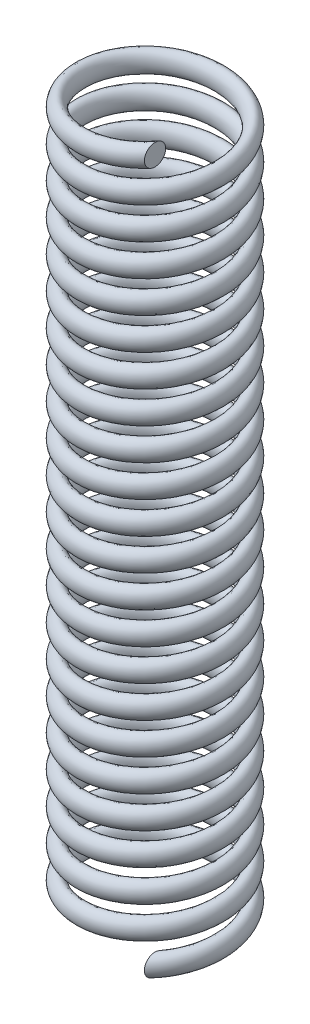
SolidWorks part; units mm, degrees
ref_plane "Front Plane" through (0, 0, 0) normal (0, 0, 1) x (1, 0, 0)
ref_plane "Top Plane" through (0, 0, 0) normal (0, 1, 0) x (1, 0, 0)
ref_plane "Right Plane" through (0, 0, 0) normal (1, 0, 0) x (0, 0, -1)
sketch "Sketch1" plane through (0, 0, 0) normal (0, 0, 1) x (1, 0, 0)
  line L0 (0, 17.5312) -> (0, -15.4688)
  dimension "D1" = 33
ref_plane "Plane1" through (0, 17.5312, 0) normal (0, 1, 0) x (1, 0, 0)
sketch "Sketch2" plane through (0, 17.5312, 0) normal (0, 1, 0) x (1, 0, 0)
  circle A0 centre (0, 0) radius 3.25
  dimension "D1" = 6.5
curve "Helix/Spiral1" pitch 1.5 height 33 turns 22
ref_plane "Plane2" through (2.2981, 0, 0) normal (1, 0, 0) x (0, 0, -1)
sketch "Sketch3" plane through (2.2981, 0, 0) normal (1, 0, 0) x (0, 0, -1)
  line L0 (3.6681, 17.5312) -> (-3.6681, 17.5312) construction
  circle A0 centre (-2.2981, 17.5312) radius 0.5
  spline S0 degree 3 poles (-2.2981, 17.5312) (-2.597, 17.5002) (-3.0817, 17.4374) (-3.3344, 17.3438) (-3.0808, 17.25) (-2.3579, 17.1563) (-1.2761, 17.0625) (0, 16.9688) (1.2761, 16.875) (2.3579, 16.7813) (3.0808, 16.6875) (3.3346, 16.5938) (3.0808, 16.5) (2.3579, 16.4063) (1.2761, 16.3125) (0, 16.2188) (-1.2761, 16.125) (-2.3579, 16.0313) (-3.0808, 15.9375) (-3.3346, 15.8438) (-3.0808, 15.75) (-2.3579, 15.6562) (-1.2761, 15.5625) (0, 15.4687) (1.2761, 15.375) (2.3579, 15.2813) (3.0808, 15.1875) (3.3346, 15.0938) (3.0808, 15) (2.3579, 14.9062) (1.2761, 14.8125) (0, 14.7188) (-1.2761, 14.625) (-2.3579, 14.5312) (-3.0808, 14.4375) (-3.3346, 14.3437) (-3.0808, 14.25) (-2.3579, 14.1563) (-1.2761, 14.0625) (0, 13.9688) (1.2761, 13.875) (2.3579, 13.7812) (3.0808, 13.6875) (3.3346, 13.5938) (3.0808, 13.5) (2.3579, 13.4062) (1.2761, 13.3125) (0, 13.2187) (-1.2761, 13.125) (-2.3579, 13.0312) (-3.0808, 12.9375) (-3.3346, 12.8437) (-3.0808, 12.75) (-2.3579, 12.6562) (-1.2761, 12.5625) (0, 12.4687) (1.2761, 12.375) (2.3579, 12.2812) (3.0808, 12.1875) (3.3346, 12.0938) (3.0808, 12) (2.3579, 11.9062) (1.2761, 11.8125) (0, 11.7187) (-1.2761, 11.625) (-2.3579, 11.5312) (-3.0808, 11.4375) (-3.3346, 11.3437) (-3.0808, 11.25) (-2.3579, 11.1562) (-1.2761, 11.0625) (0, 10.9687) (1.2761, 10.875) (2.3579, 10.7812) (3.0808, 10.6875) (3.3346, 10.5937) (3.0808, 10.5) (2.3579, 10.4062) (1.2761, 10.3125) (0, 10.2187) (-1.2761, 10.125) (-2.3579, 10.0312) (-3.0808, 9.9375) (-3.3346, 9.8437) (-3.0808, 9.75) (-2.3579, 9.6562) (-1.2761, 9.5625) (0, 9.4687) (1.2761, 9.375) (2.3579, 9.2812) (3.0808, 9.1875) (3.3346, 9.0937) (3.0808, 9) (2.3579, 8.9062) (1.2761, 8.8125) (0, 8.7187) (-1.2761, 8.625) (-2.3579, 8.5312) (-3.0808, 8.4375) (-3.3346, 8.3437) (-3.0808, 8.25) (-2.3579, 8.1562) (-1.2761, 8.0625) (0, 7.9687) (1.2761, 7.875) (2.3579, 7.7812) (3.0808, 7.6875) (3.3346, 7.5937) (3.0808, 7.5) (2.3579, 7.4062) (1.2761, 7.3125) (0, 7.2187) (-1.2761, 7.125) (-2.3579, 7.0312) (-3.0808, 6.9375) (-3.3346, 6.8437) (-3.0808, 6.75) (-2.3579, 6.6562) (-1.2761, 6.5625) (0, 6.4687) (1.2761, 6.375) (2.3579, 6.2812) (3.0808, 6.1875) (3.3346, 6.0937) (3.0808, 6) (2.3579, 5.9062) (1.2761, 5.8125) (0, 5.7187) (-1.2761, 5.625) (-2.3579, 5.5312) (-3.0808, 5.4375) (-3.3346, 5.3437) (-3.0808, 5.25) (-2.3579, 5.1562) (-1.2761, 5.0625) (0, 4.9687) (1.2761, 4.875) (2.3579, 4.7812) (3.0808, 4.6875) (3.3346, 4.5937) (3.0808, 4.5) (2.3579, 4.4062) (1.2761, 4.3125) (0, 4.2187) (-1.2761, 4.125) (-2.3579, 4.0312) (-3.0808, 3.9375) (-3.3346, 3.8437) (-3.0808, 3.75) (-2.3579, 3.6562) (-1.2761, 3.5625) (0, 3.4687) (1.2761, 3.375) (2.3579, 3.2812) (3.0808, 3.1875) (3.3346, 3.0937) (3.0808, 3) (2.3579, 2.9062) (1.2761, 2.8125) (0, 2.7187) (-1.2761, 2.625) (-2.3579, 2.5312) (-3.0808, 2.4375) (-3.3346, 2.3437) (-3.0808, 2.25) (-2.3579, 2.1562) (-1.2761, 2.0625) (0, 1.9687) (1.2761, 1.875) (2.3579, 1.7812) (3.0808, 1.6875) (3.3346, 1.5937) (3.0808, 1.5) (2.3579, 1.4062) (1.2761, 1.3125) (0, 1.2187) (-1.2761, 1.125) (-2.3579, 1.0312) (-3.0808, 0.9375) (-3.3346, 0.8437) (-3.0808, 0.75) (-2.3579, 0.6562) (-1.2761, 0.5625) (0, 0.4687) (1.2761, 0.375) (2.3579, 0.2812) (3.0808, 0.1875) (3.3346, 0.0937) (3.0808, 0) (2.3579, -0.0938) (1.2761, -0.1875) (0, -0.2813) (-1.2761, -0.375) (-2.3579, -0.4688) (-3.0808, -0.5625) (-3.3346, -0.6563) (-3.0808, -0.75) (-2.3579, -0.8438) (-1.2761, -0.9375) (0, -1.0313) (1.2761, -1.125) (2.3579, -1.2188) (3.0808, -1.3125) (3.3346, -1.4063) (3.0808, -1.5) (2.3579, -1.5938) (1.2761, -1.6875) (0, -1.7813) (-1.2761, -1.875) (-2.3579, -1.9688) (-3.0808, -2.0625) (-3.3346, -2.1563) (-3.0808, -2.25) (-2.3579, -2.3438) (-1.2761, -2.4375) (0, -2.5313) (1.2761, -2.625) (2.3579, -2.7188) (3.0808, -2.8125) (3.3346, -2.9063) (3.0808, -3) (2.3579, -3.0938) (1.2761, -3.1875) (0, -3.2813) (-1.2761, -3.375) (-2.3579, -3.4688) (-3.0808, -3.5625) (-3.3346, -3.6563) (-3.0808, -3.75) (-2.3579, -3.8438) (-1.2761, -3.9375) (0, -4.0313) (1.2761, -4.125) (2.3579, -4.2188) (3.0808, -4.3125) (3.3346, -4.4063) (3.0808, -4.5) (2.3579, -4.5938) (1.2761, -4.6875) (0, -4.7813) (-1.2761, -4.875) (-2.3579, -4.9688) (-3.0808, -5.0625) (-3.3346, -5.1563) (-3.0808, -5.25) (-2.3579, -5.3438) (-1.2761, -5.4375) (0, -5.5313) (1.2761, -5.625) (2.3579, -5.7188) (3.0808, -5.8125) (3.3346, -5.9063) (3.0808, -6) (2.3579, -6.0938) (1.2761, -6.1875) (0, -6.2813) (-1.2761, -6.375) (-2.3579, -6.4688) (-3.0808, -6.5625) (-3.3346, -6.6563) (-3.0808, -6.75) (-2.3579, -6.8438) (-1.2761, -6.9375) (0, -7.0313) (1.2761, -7.125) (2.3579, -7.2188) (3.0808, -7.3125) (3.3346, -7.4063) (3.0808, -7.5) (2.3579, -7.5938) (1.2761, -7.6875) (0, -7.7813) (-1.2761, -7.875) (-2.3579, -7.9688) (-3.0808, -8.0625) (-3.3346, -8.1563) (-3.0808, -8.25) (-2.3579, -8.3438) (-1.2761, -8.4375) (0, -8.5313) (1.2761, -8.625) (2.3579, -8.7188) (3.0808, -8.8125) (3.3346, -8.9063) (3.0808, -9) (2.3579, -9.0938) (1.2761, -9.1875) (0, -9.2813) (-1.2761, -9.375) (-2.3579, -9.4688) (-3.0808, -9.5625) (-3.3346, -9.6563) (-3.0808, -9.75) (-2.3579, -9.8438) (-1.2761, -9.9375) (0, -10.0313) (1.2761, -10.125) (2.3579, -10.2188) (3.0808, -10.3125) (3.3346, -10.4063) (3.0808, -10.5) (2.3579, -10.5938) (1.2761, -10.6875) (0, -10.7813) (-1.2761, -10.875) (-2.3579, -10.9688) (-3.0808, -11.0625) (-3.3346, -11.1563) (-3.0808, -11.25) (-2.3579, -11.3438) (-1.2761, -11.4375) (0, -11.5313) (1.2761, -11.625) (2.3579, -11.7188) (3.0808, -11.8125) (3.3346, -11.9063) (3.0808, -12) (2.3579, -12.0938) (1.2761, -12.1875) (0, -12.2813) (-1.2761, -12.375) (-2.3579, -12.4688) (-3.0808, -12.5625) (-3.3346, -12.6563) (-3.0808, -12.75) (-2.3579, -12.8438) (-1.2761, -12.9375) (0, -13.0313) (1.2761, -13.125) (2.3579, -13.2188) (3.0808, -13.3125) (3.3346, -13.4063) (3.0808, -13.5) (2.3579, -13.5938) (1.2761, -13.6875) (0, -13.7813) (-1.2761, -13.875) (-2.3579, -13.9688) (-3.0808, -14.0625) (-3.3346, -14.1563) (-3.0808, -14.25) (-2.3579, -14.3438) (-1.2761, -14.4375) (0, -14.5313) (1.2761, -14.625) (2.3579, -14.7188) (3.0808, -14.8125) (3.3346, -14.9063) (3.0808, -15) (2.3579, -15.0938) (1.2762, -15.1875) (-0.0002, -15.2813) (-1.2752, -15.3749) (-1.9992, -15.4377) (-2.2981, -15.4687) knots 0 0 0 0 0.002841 0.005682 0.008523 0.011364 0.014205 0.017045 0.019886 0.022727 0.025568 0.028409 0.03125 0.034091 0.036932 0.039773 0.042614 0.045455 0.048295 0.051136 0.053977 0.056818 0.059659 0.0625 0.065341 0.068182 0.071023 0.073864 0.076705 0.079545 0.082386 0.085227 0.088068 0.090909 0.09375 0.096591 0.099432 0.102273 0.105114 0.107955 0.110795 0.113636 0.116477 0.119318 0.122159 0.125 0.127841 0.130682 0.133523 0.136364 0.139205 0.142045 0.144886 0.147727 0.150568 0.153409 0.15625 0.159091 0.161932 0.164773 0.167614 0.170455 0.173295 0.176136 0.178977 0.181818 0.184659 0.1875 0.190341 0.193182 0.196023 0.198864 0.201705 0.204545 0.207386 0.210227 0.213068 0.215909 0.21875 0.221591 0.224432 0.227273 0.230114 0.232955 0.235795 0.238636 0.241477 0.244318 0.247159 0.25 0.252841 0.255682 0.258523 0.261364 0.264205 0.267045 0.269886 0.272727 0.275568 0.278409 0.28125 0.284091 0.286932 0.289773 0.292614 0.295455 0.298295 0.301136 0.303977 0.306818 0.309659 0.3125 0.315341 0.318182 0.321023 0.323864 0.326705 0.329545 0.332386 0.335227 0.338068 0.340909 0.34375 0.346591 0.349432 0.352273 0.355114 0.357955 0.360795 0.363636 0.366477 0.369318 0.372159 0.375 0.377841 0.380682 0.383523 0.386364 0.389205 0.392045 0.394886 0.397727 0.400568 0.403409 0.40625 0.409091 0.411932 0.414773 0.417614 0.420455 0.423295 0.426136 0.428977 0.431818 0.434659 0.4375 0.440341 0.443182 0.446023 0.448864 0.451705 0.454545 0.457386 0.460227 0.463068 0.465909 0.46875 0.471591 0.474432 0.477273 0.480114 0.482955 0.485795 0.488636 0.491477 0.494318 0.497159 0.5 0.502841 0.505682 0.508523 0.511364 0.514205 0.517045 0.519886 0.522727 0.525568 0.528409 0.53125 0.534091 0.536932 0.539773 0.542614 0.545455 0.548295 0.551136 0.553977 0.556818 0.559659 0.5625 0.565341 0.568182 0.571023 0.573864 0.576705 0.579545 0.582386 0.585227 0.588068 0.590909 0.59375 0.596591 0.599432 0.602273 0.605114 0.607955 0.610795 0.613636 0.616477 0.619318 0.622159 0.625 0.627841 0.630682 0.633523 0.636364 0.639205 0.642045 0.644886 0.647727 0.650568 0.653409 0.65625 0.659091 0.661932 0.664773 0.667614 0.670455 0.673295 0.676136 0.678977 0.681818 0.684659 0.6875 0.690341 0.693182 0.696023 0.698864 0.701705 0.704545 0.707386 0.710227 0.713068 0.715909 0.71875 0.721591 0.724432 0.727273 0.730114 0.732955 0.735795 0.738636 0.741477 0.744318 0.747159 0.75 0.752841 0.755682 0.758523 0.761364 0.764205 0.767045 0.769886 0.772727 0.775568 0.778409 0.78125 0.784091 0.786932 0.789773 0.792614 0.795455 0.798295 0.801136 0.803977 0.806818 0.809659 0.8125 0.815341 0.818182 0.821023 0.823864 0.826705 0.829545 0.832386 0.835227 0.838068 0.840909 0.84375 0.846591 0.849432 0.852273 0.855114 0.857955 0.860795 0.863636 0.866477 0.869318 0.872159 0.875 0.877841 0.880682 0.883523 0.886364 0.889205 0.892045 0.894886 0.897727 0.900568 0.903409 0.90625 0.909091 0.911932 0.914773 0.917614 0.920455 0.923295 0.926136 0.928977 0.931818 0.934659 0.9375 0.940341 0.943182 0.946023 0.948864 0.951705 0.954545 0.957386 0.960227 0.963068 0.965909 0.96875 0.971591 0.974432 0.977273 0.980114 0.982955 0.985795 0.988636 0.991477 0.994318 0.997159 1 1 1 1 construction
  dimension "D1" = 1
sweep "Sweep1" add profiles "Sketch3" path "Helix/Spiral1"
sketch "Sketch4" plane through (0, 17.5312, 0) normal (0, 1, 0) x (1, 0, 0)
  circle A0 centre (0, 0) radius 3.6301
